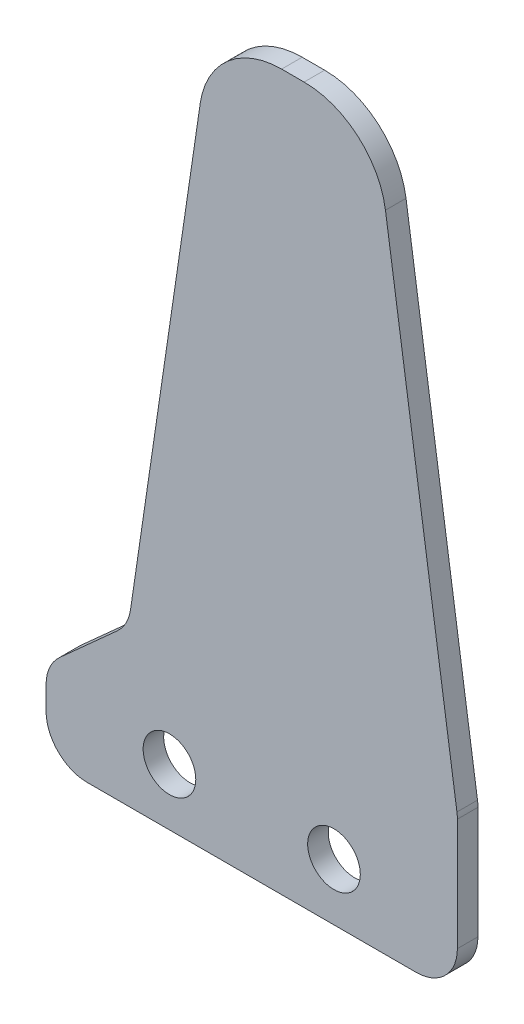
SolidWorks part; units mm, degrees
ref_plane "Front Plane" through (0, 0, 0) normal (0, 0, 1) x (1, 0, 0)
ref_plane "Top Plane" through (0, 0, 0) normal (0, 1, 0) x (1, 0, 0)
ref_plane "Right Plane" through (0, 0, 0) normal (1, 0, 0) x (0, 0, -1)
sketch "Sketch1" plane through (0, 0, 0) normal (0, 0, 1) x (1, 0, 0)
  line L0 (9.525, -4.3924) -> (9.525, 7.6715)
  line L1 (9.525, 7.6715) -> (3.175, 50.8)
  line L2 (3.175, 50.8) -> (-9.525, 50.8)
  line L3 (-9.525, 50.8) -> (-15.875, 7.6715)
  line L5 (-22.225, -4.3924) -> (9.525, -4.3924)
  line L6 (9.525, -1.374) -> (9.525, 7.317) construction
  line L7 (-23.8585, -4.3924) -> (5.9891, -4.3924) construction
  line L8 (-13.7574, 7.6715) -> (11.0676, 7.6715) construction
  line L9 (-15.875, 7.6715) -> (-22.225, 1.9576)
  line L10 (-22.225, 1.9576) -> (-22.225, -4.3924)
  circle A0 centre (0, 0) radius 2.032
  circle A1 centre (-12.7, 0) radius 2.032
  circle A2 centre (-12.7, 0) radius 1.905 construction
  dimension "D1" = 4.064
  dimension "D2" = 50.8
  dimension "D3" = 31.75
  dimension "D4" = 12.7
  dimension "D5" = 6.35
  dimension "D6" = 25.4
extrude "Boss-Extrude1" add sketch "Sketch1" along normal blind 1.5875
fillet "Fillet1" radius 6.35 2 edges at (-9.525, 50.8, 0.7937) (3.175, 50.8, 0.7937)
fillet "Fillet2" radius 3.175 5 edges at (9.525, 7.6715, 0.7937) (9.525, -4.3924, 0.7937) (-22.225, -4.3924, 0.7937) (-22.225, 1.9576, 0.7937) (-15.875, 7.6715, 0.7937)
